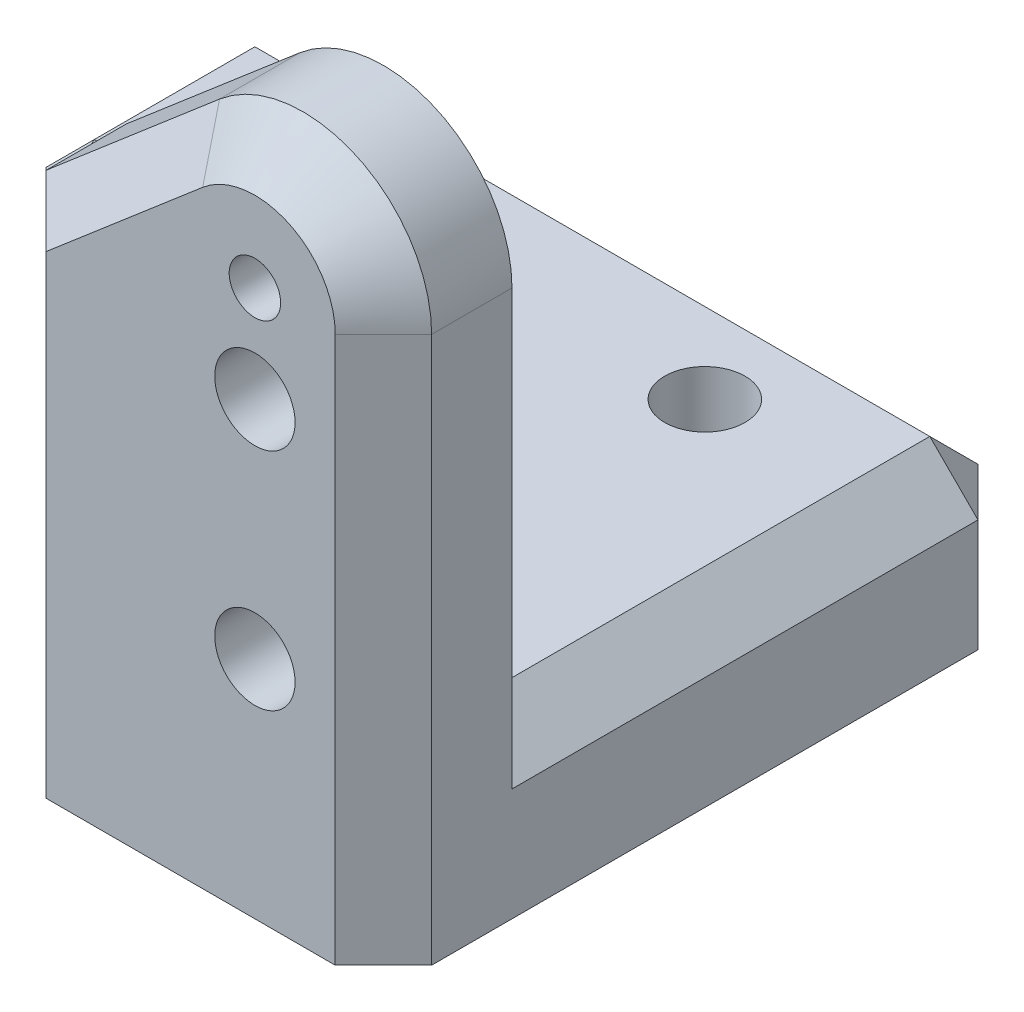
SolidWorks part; units mm, degrees
ref_plane "Plano frontal" through (0, 0, 0) normal (0, 0, 1) x (1, 0, 0)
ref_plane "Plano superior" through (0, 0, 0) normal (0, 1, 0) x (1, 0, 0)
ref_plane "Plano direito" through (0, 0, 0) normal (1, 0, 0) x (0, 0, -1)
sketch "Esboço1" plane through (0, 0, 0) normal (0, 0, 1) x (1, 0, 0)
  line L0 (0, 0) -> (0, 12)
  line L1 (0, 12) -> (9.4001, 20.0398)
  line L4 (16, 17) -> (16, 4)
  line L5 (16, 4) -> (16, 0)
  line L6 (16, 0) -> (0, 0)
  arc A0 (9.4001, 20.0398) -> (16, 17) centre (12, 17) cw
  point P19 (12, 17)
  dimension "D1" = 4
  dimension "D2" = 16
  dimension "D3" = 12
  dimension "D4" = 16
  dimension "D5" = 4
  dimension "D6" = 17
extrude "Ressalto-extrusão1" add sketch "Esboço1" along normal blind 20
sketch "Esboço2" plane through (16, 0, 0) normal (1, 0, 0) x (0, 0, -1)
  line L0 (-20, 0) -> (-20, 5) construction
  line L1 (-20, 5) -> (0, 5) construction
  line L4 (0, 5) -> (-16, 5)
  line L5 (0, 5) -> (0, 21)
  line L6 (0, 21) -> (-16, 21)
  line L7 (-16, 5) -> (-16, 21)
  line L8 (0, 21) -> (-20, 21) construction
  line L9 (0, 0) -> (0, 17) construction
  dimension "D1" = 16
  dimension "D2" = 5
extrude "Corte-extrusão1" cut sketch "Esboço2" against normal blind 20
sketch "Esboço3" plane through (0, 0, 20) normal (0, 0, 1) x (1, 0, 0)
  line L0 (0, 0) -> (4, 0)
  line L1 (0, 0) -> (16, 0) construction
  line L2 (4, 0) -> (4, 15.4212)
  line L3 (9.4001, 20.0398) -> (0, 12) construction
  line L4 (4, 15.4212) -> (0, 12)
  line L5 (0, 12) -> (0, 0)
  dimension "D1" = 4
extrude "Corte-extrusão2" cut sketch "Esboço3" against normal through all
chamfer "Chanfro2" distance 1.5 angle 45 4 edges at (16, 8.5, 20) (13.6734, 20.6332, 20) (6.7, 17.7305, 20) (4, 7.7106, 20)
sketch "Esboço4" plane through (0, 0, 20) normal (0, 0, 1) x (1, 0, 0)
  line L0 (9.4001, 20.0398) -> (12, 17) construction
  point P5 (12, 17)
hole_wizard "Furo roscado de M21" positions "3DSketch1" profile "Esboço5" tap size "M2" standard "ISO" end condition through all
sketch3d "3DSketch1"
  point P0 (12, 17, 20)
sketch "Esboço5" plane through (12, 17, 20) normal (1, 0, 0) x (0, -1, 0)
  line L0 (0, 0) -> (0, 20)
  line L1 (0, 20) -> (0.8, 20)
  line L2 (0.8, 20) -> (0.8, 0)
  line L5 (0.8, 0) -> (0, 0)
  line L11 (0, -6.35) -> (0, 107.95) construction
  dimension "Thru Tap Drill Dia." = 1.6
  dimension "Thru Tap Drill Depth" = 20
cosmetic thread "Rosca de furo1" parameters "D2"=2
sketch "Esboço8" plane through (4, 0, 0) normal (-1, 0, 0) x (0, 0, 1)
  line L0 (0, 5) -> (8, 5)
  line L1 (0, 5) -> (16, 5) construction
  line L2 (8, 5) -> (8, 0)
  line L3 (0, 0) -> (18.5, 0) construction
  line L4 (8, 0) -> (0, 0)
  line L5 (0, 0) -> (0, 5)
  dimension "D1" = 8
extrude "Ressalto-extrusão2" add sketch "Esboço8" along normal blind 12
chamfer "Chanfro3" distance 1.5 angle 45 9 edges at (16, 5, 8) (16, 2.5, 0) (4, 5, 0) (-8, 2.5, 0) (-8, 5, 4) (-8, 2.5, 8) (-2, 5, 8) (4, 5, 12) (4, 2.5, 8)
sketch "Esboço9" plane through (0, 0, 0) normal (0, -1, 0) x (1, 0, 0)
  line L0 (10, 20) -> (10, 0) construction
  line L1 (5.5, 20) -> (14.5, 20) construction
  line L2 (-6.5, 0) -> (14.5, 0) construction
  line L3 (-8, 4) -> (10, 4) construction
  line L4 (-8, 1.5) -> (-8, 6.5) construction
  line L5 (10, 4) -> (16, 4) construction
  line L6 (16, 18.5) -> (16, 1.5) construction
  point P10 (10, 14)
  point P15 (4, 4)
  point P16 (-2, 4)
  point P23 (10, 9)
  dimension "D1" = 6
  dimension "D2" = 6
  dimension "D3" = 6
  dimension "D4" = 5
hole_wizard "Furo roscado de M31" positions "3DSketch2" profile "Esboço10" tap size "M3" standard "ISO"
sketch3d "3DSketch2"
  point P0 (-2, 0, 4)
  point P6 (10, 0, 4)
  point P12 (10, 0, 14)
sketch "Esboço10" plane through (-2, 0, 4) normal (1, 0, 0) x (0, 0, -1)
  line L0 (0, 0) -> (0, 9.2511)
  line L1 (0, 9.2511) -> (1.25, 8.5)
  line L2 (1.25, 8.5) -> (1.25, 0)
  line L5 (1.25, 0) -> (0, 0)
  line L10 (0, 9.2511) -> (-1.25, 8.5) construction
  line L11 (0, -6.35) -> (0, 107.95) construction
  dimension "Tap Drill Dia." = 2.5
  dimension "Tap Drill Depth" = 8.5
  dimension "Drill Angle" = 118
cosmetic thread "Rosca de furo2" parameters "D1"=5, "D2"=3
cosmetic thread "Rosca de furo4" parameters "D1"=5, "D2"=3
cosmetic thread "Rosca de furo6" parameters "D1"=5, "D2"=3
sketch "Esboço11" plane through (0, 0, 20) normal (0, 0, 1) x (1, 0, 0)
  line L0 (16, 17) -> (16, 0) construction
  line L1 (5.5, 0) -> (14.5, 0) construction
  line L2 (12, 7) -> (12, 14) construction
  point P0 (12, 7)
  dimension "D1" = 4
  dimension "D2" = 7
  dimension "D3" = 7
hole_wizard "Broca de rosquear para tarraxa de M31" positions "3DSketch3" profile "Esboço12" hole size "M3" standard "ISO" end condition up to next
sketch3d "3DSketch3"
  point P0 (12, 7, 20)
  point P3 (12, 14, 20)
sketch "Esboço12" plane through (12, 7, 20) normal (1, 0, 0) x (0, -1, 0)
  line L0 (0, 0) -> (0, 4)
  line L1 (0, 4) -> (1.25, 4)
  line L2 (1.25, 4) -> (1.25, 0)
  line L5 (1.25, 0) -> (0, 0)
  line L11 (0, -6.35) -> (0, 107.95) construction
  dimension "Thru Hole Dia." = 2.5
  dimension "Thru Hole Depth" = 4
